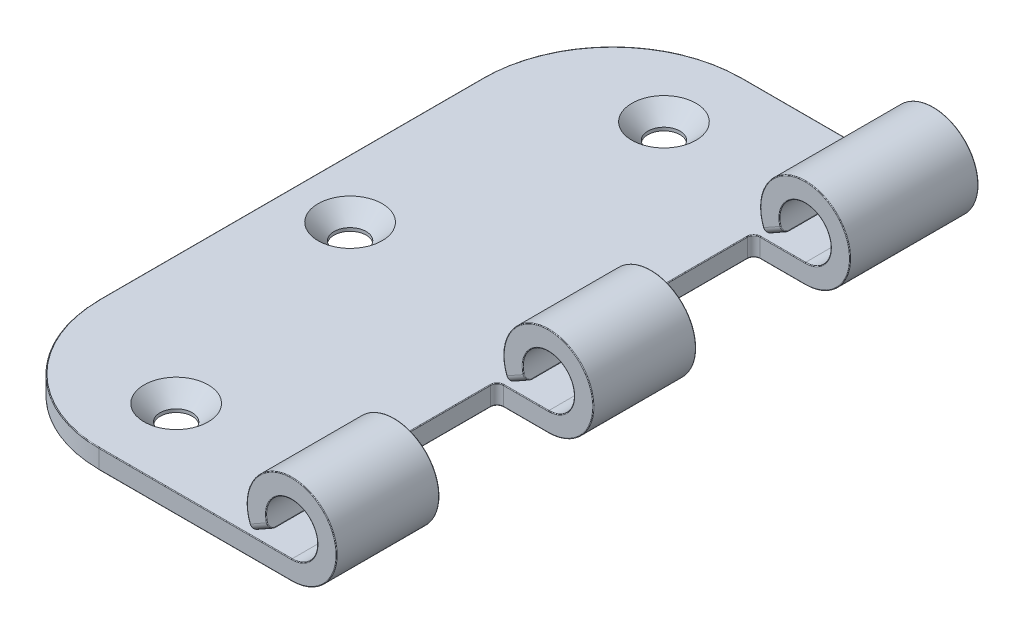
SolidWorks part; units mm, degrees
ref_plane "Front" through (0, 0, 0) normal (0, 0, 1) x (1, 0, 0)
ref_plane "Top" through (0, 0, 0) normal (0, 1, 0) x (1, 0, 0)
ref_plane "Right" through (0, 0, 0) normal (1, 0, 0) x (0, 0, -1)
sketch "Sketch1" plane through (0, 0, 0) normal (0, 0, 1) x (1, 0, 0)
  line L1 (0, -7) -> (-50, -7)
  line L2 (-50, -7) -> (-50, -4)
  line L3 (0, -4) -> (-50, -4)
  line L4 (-3.4801, -1.9721) -> (-6.0902, -3.4511)
  arc A0 (0, -4) -> (-3.4801, -1.9721) centre (0, 0) ccw
  arc A1 (0, -7) -> (-6.0902, -3.4511) centre (0, 0) ccw
  circle A3 centre (0, 0) radius 7 construction
  circle A4 centre (0, 0) radius 4 construction
  point P4 (3.8252, 1.1695)
  point P11 (7, 0)
  dimension "D1" = 8
  dimension "D3" = 50
  dimension "D2" = 3
extrude "Boss-Extrude1" add sketch "Sketch1" along normal blind 100
sketch "Sketch2" plane through (0, -4, 0) normal (0, 1, 0) x (1, 0, 0)
  line L0 (7, 0) -> (-7, 0) construction
  line L1 (9.5127, -20) -> (-8, -20)
  line L2 (9.5127, -20) -> (9.5127, -44)
  line L3 (9.5127, -44) -> (-8, -44)
  line L4 (-8, -20) -> (-8, -44)
  line L5 (13.4352, -60) -> (-8, -60)
  line L6 (13.4352, -60) -> (13.4352, -84)
  line L7 (13.4352, -84) -> (-8, -84)
  line L8 (-8, -60) -> (-8, -84)
  line L9 (0, 0) -> (-50, 0) construction
  line L10 (7, -100) -> (7, 0) construction
  dimension "D1" = 20
  dimension "D2" = 24
  dimension "D3" = 60
  dimension "D4" = 24
  dimension "D5" = 15
  dimension "D6" = 15
extrude "Cut-Extrude1" cut sketch "Sketch2" against normal blind 73 and the other way blind 84
fillet "Fillet1" radius 1 4 edges at (-8, -5.5, 84) (-8, -5.5, 60) (-8, -5.5, 44) (-8, -5.5, 20)
fillet "Fillet2" radius 20 2 edges at (-50, -5.5, 100) (-50, -5.5, 0)
sketch "Sketch4" plane through (0, -4, 0) normal (0, 1, 0) x (1, 0, 0)
  line L0 (0, 0) -> (-30, 0) construction
  circle A0 centre (-30, -12) radius 2.5
  circle A1 centre (-40.8984, -50) radius 2.5
  circle A2 centre (-30, -88) radius 2.5
  dimension "D1" = 5
  dimension "D2" = 12
extrude "Cut-Extrude2" cut sketch "Sketch4" against normal blind 4
chamfer "Chamfer1" distance 2.5 angle 45 3 edges at (-30, -4, 85.5) (-40.8984, -4, 52.5) (-30, -4, 14.5)
fillet "Fillet3" radius 1 6 edges at (-4.7851, -2.7116, 0) (-4.7851, -2.7116, 44) (-4.7851, -2.7116, 84) (-4.7851, -2.7116, 100) (-4.7851, -2.7116, 60) (-4.7851, -2.7116, 20)
fillet "Fillet4" radius 0.1 60 edges at (-44.1421, -7, 94.1421) (-50, -7, 50) (-44.1421, -7, 5.8579) (-15, -7, 0) (3.9484, 5.7801, 0) (-6.2677, -3.1171, 0.2169) (-6.0902, -3.4511, 10) (-6.1952, -3.2588, 19.6246) (3.9484, 5.7801, 20) (-3.5, -7, 20) (-7.7071, -7, 20.2929) (-8, -7, 32) (-7.7071, -7, 43.7071) (-3.5, -7, 44) (3.9484, 5.7801, 44) (-6.2677, -3.1171, 44.2169) (-6.0902, -3.4511, 52) (-6.1952, -3.2588, 59.6246) (3.9484, 5.7801, 60) (-3.5, -7, 60) (-7.7071, -7, 60.2929) (-8, -7, 72) (-7.7071, -7, 83.7071) (-3.5, -7, 84) (3.9484, 5.7801, 84) (-6.2677, -3.1171, 84.2169) (-6.0902, -3.4511, 92) (-6.1952, -3.2588, 99.6246) (3.9484, 5.7801, 100) (2.4333, 3.1747, 100) (-3.6533, -1.6289, 99.7877) (-3.4801, -1.9721, 92) (-3.5828, -1.7787, 84.3756) (2.4333, 3.1747, 84) (-3.5, -4, 84) (-7.7071, -4, 83.7071) (-8, -4, 72) (-7.7071, -4, 60.2929) (-3.5, -4, 60) (2.4333, 3.1747, 60) (-3.6533, -1.6289, 59.7877) (-3.4801, -1.9721, 52) (-3.5828, -1.7787, 44.3756) (2.4333, 3.1747, 44) (-3.5, -4, 44) (-7.7071, -4, 43.7071) (-8, -4, 32) (-7.7071, -4, 20.2929) (-3.5, -4, 20) (2.4333, 3.1747, 20) (-3.6533, -1.6289, 19.7877) (-3.4801, -1.9721, 10) (-3.5828, -1.7787, 0.3756) (2.4333, 3.1747, 0) (-15, -4, 0) (-44.1421, -4, 5.8579) (-50, -4, 50) (-44.1421, -4, 94.1421) (-15, -7, 100) (-15, -4, 100)
